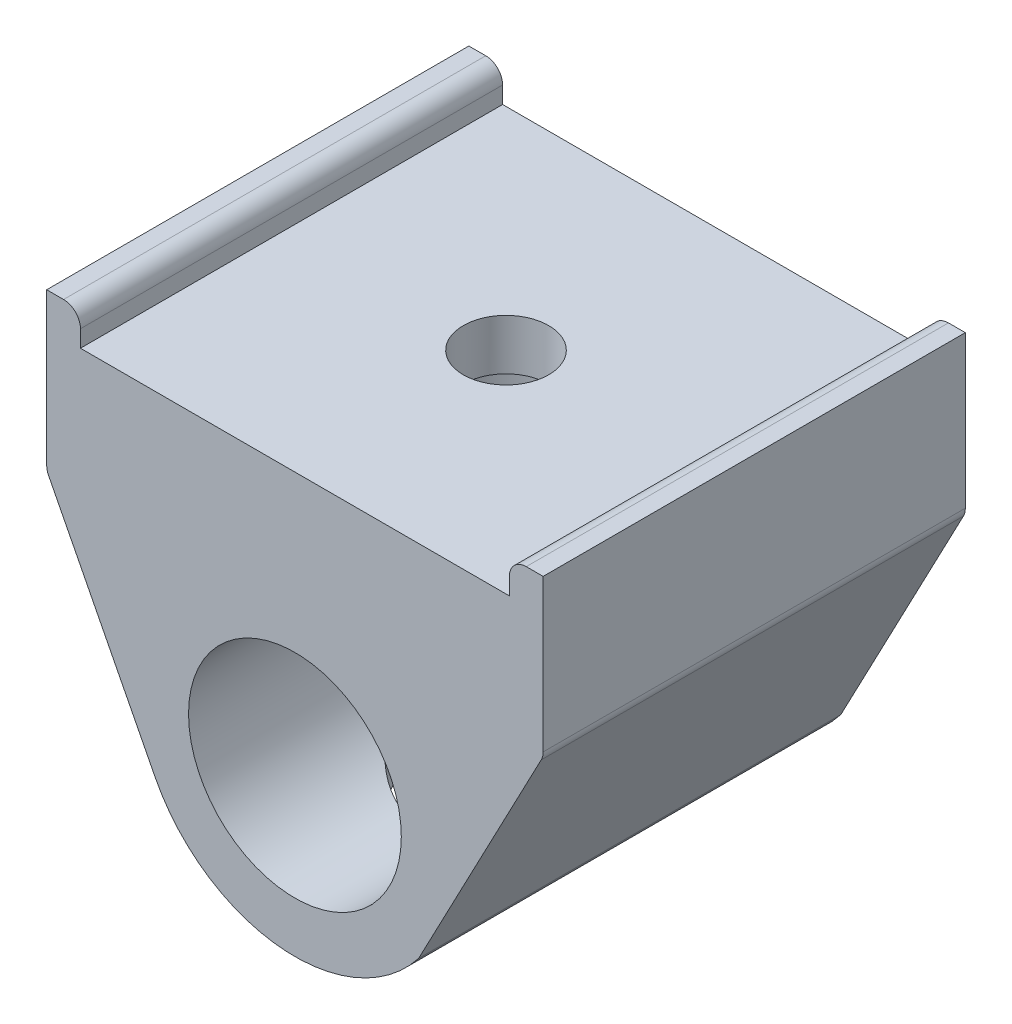
SolidWorks part; units mm, degrees
ref_plane "Front Plane" through (0, 0, 0) normal (0, 0, 1) x (1, 0, 0)
ref_plane "Top Plane" through (0, 0, 0) normal (0, 1, 0) x (1, 0, 0)
ref_plane "Right Plane" through (0, 0, 0) normal (1, 0, 0) x (0, 0, -1)
sketch "Sketch1" plane through (0, 0, 0) normal (0, 0, 1) x (1, 0, 0)
  line L0 (-14.7, 8.3) -> (-8.2774, -4.2396)
  line L1 (14.7, 15.55) -> (-14.7, 15.55)
  line L2 (14.7, 15.55) -> (14.7, 8.3)
  line L3 (14.7, 8.3) -> (-14.7, 8.3)
  line L4 (-14.7, 15.55) -> (-14.7, 8.3)
  line L5 (14.7, 15.55) -> (-14.7, 8.3) construction
  line L6 (14.7, 8.3) -> (-14.7, 15.55) construction
  line L7 (14.7, 8.3) -> (7.3258, -5.7291)
  circle A0 centre (0, 0) radius 6.3
  circle A1 centre (0, 0) radius 9.3
  point P4 (0, 11.925)
  dimension "D1" = 12.6
  dimension "D2" = 3
  dimension "D4" = 8.3
  dimension "D3" = 7.25
  dimension "D5" = 29.4
  dimension "D6" = 0
extrude "Boss-Extrude1" add sketch "Sketch1" along normal blind 25 contours A1 L3 L2 L1 L4 | A1 L3 L0 | L3 A1 L7 A0 | L3 A1 | A1 L7 L3
sketch "Sketch2" plane through (0, 15.55, 0) normal (0, 1, 0) x (1, 0, 0)
  line L0 (14.7, -25) -> (14.7, 0) construction
  point P0 (0, -12.5)
  point P3 (14.7, -12.5)
  dimension "D1" = 0
hole_wizard "#8 (0.199) Diameter Hole1" positions "Sketch3" profile "Sketch4" hole size "#8" standard "ANSI Inch" end condition through all
sketch "Sketch3" plane through (0, 15.55, 0) normal (0, 1, 0) x (1, 0, 0)
  point P0 (0, -12.5)
sketch "Sketch4" plane through (0, 15.55, 12.5) normal (1, 0, 0) x (0, 0, 1)
  line L0 (0, 0) -> (0, 24.85)
  line L1 (0, 24.85) -> (2.5273, 24.85)
  line L2 (2.5273, 24.85) -> (2.5273, 0)
  line L5 (2.5273, 0) -> (0, 0)
  line L11 (0, -6.35) -> (0, 107.95) construction
  dimension "Thru Hole Dia." = 5.0546
  dimension "Thru Hole Depth" = 24.85
sketch "Sketch5" plane through (0, 15.55, 0) normal (0, 1, 0) x (1, 0, 0)
  circle A0 centre (0, -12.5) radius 5.08
  dimension "D1" = 10.16
extrude "Cut-Extrude2" cut sketch "Sketch5" against normal through all from offset 3 offset against normal yes
sketch "Sketch6" plane through (0, 0, 0) normal (0, 0, -1) x (-1, 0, 0)
  line L1 (14.7, 15.55) -> (12.7, 15.55)
  line L2 (14.7, 15.55) -> (14.7, 17.55)
  line L3 (14.7, 17.55) -> (12.7, 17.55)
  line L4 (12.7, 15.55) -> (12.7, 17.55)
  line L5 (-14.7, 15.55) -> (-12.7, 15.55)
  line L6 (-14.7, 15.55) -> (-14.7, 17.55)
  line L7 (-14.7, 17.55) -> (-12.7, 17.55)
  line L8 (-12.7, 15.55) -> (-12.7, 17.55)
  dimension "D1" = 2
  dimension "D2" = 2
  dimension "D3" = 2
  dimension "D4" = 2
extrude "Boss-Extrude2" add sketch "Sketch6" against normal up to surface (25 mm away) up to face at (-0.2266, 5.5763, 25)
fillet "Fillet1" radius 1 4 edges at (-14.7, 8.3, 12.5) (14.7, 8.3, 12.5) (12.7, 17.55, 12.5) (-12.7, 17.55, 12.5)
